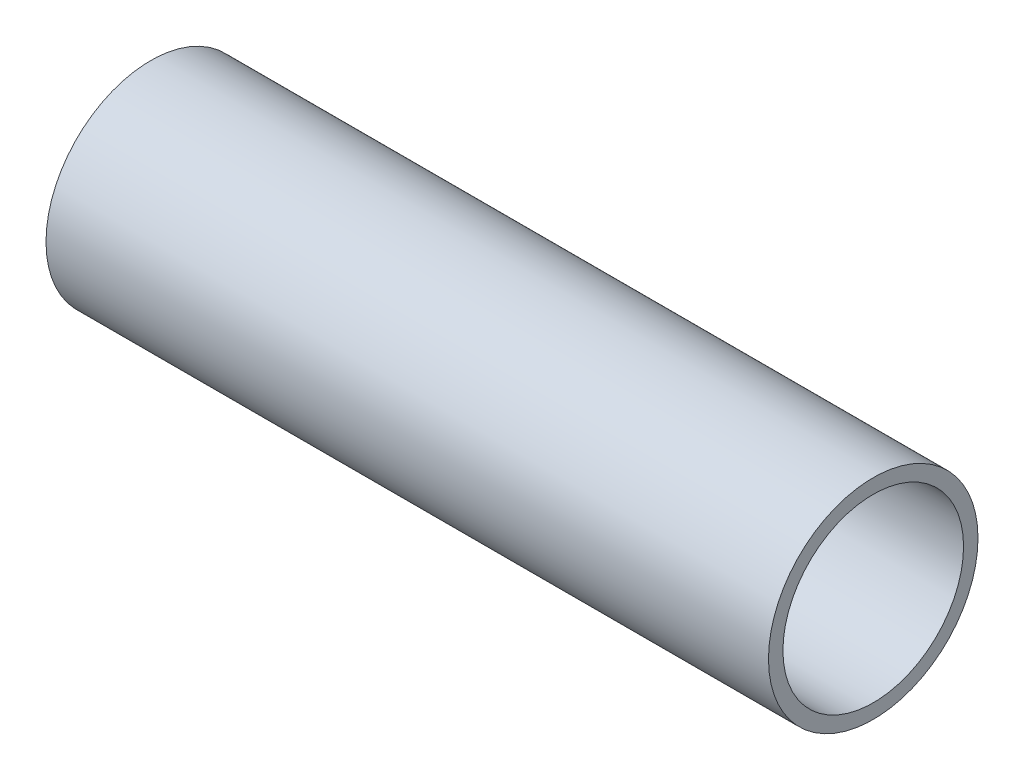
SolidWorks part; units mm, degrees
ref_plane "Front Plane" through (0, 0, 0) normal (0, 0, 1) x (1, 0, 0)
ref_plane "Top Plane" through (0, 0, 0) normal (0, 1, 0) x (1, 0, 0)
ref_plane "Right Plane" through (0, 0, 0) normal (1, 0, 0) x (0, 0, -1)
sketch "Sketch1" plane through (0, 0, 0) normal (0, 0, 1) x (1, 0, 0)
  line L0 (0, 0) -> (-103.4618, 0) construction
  line L5 (-50, 14.5) -> (50, 14.5)
  line L6 (-50, 14.5) -> (-50, 12.5)
  line L7 (-50, 12.5) -> (50, 12.5)
  line L8 (50, 14.5) -> (50, 12.5)
  line L9 (-50, 14.5) -> (50, 12.5) construction
  line L10 (-50, 12.5) -> (50, 14.5) construction
  point P0 (0, 13.5)
  dimension "D1" = 100
  dimension "D2" = 2
  dimension "D3" = 12.5
revolve "Revolve1" add sketch "Sketch1" angle 360 about L0
